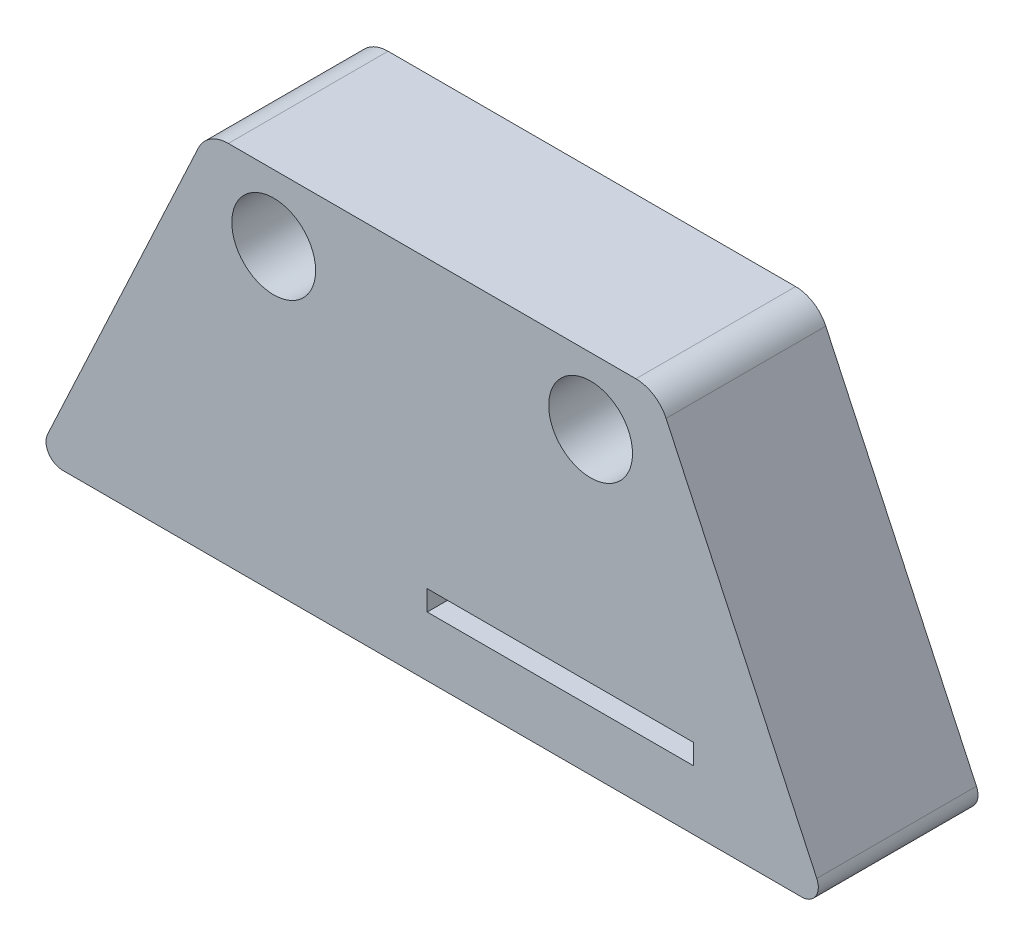
SolidWorks part; units mm, degrees
material "6061 Alloy"
ref_plane "Front Plane" through (0, 0, 0) normal (0, 0, 1) x (1, 0, 0)
ref_plane "Top Plane" through (0, 0, 0) normal (0, 1, 0) x (1, 0, 0)
ref_plane "Right Plane" through (0, 0, 0) normal (1, 0, 0) x (0, 0, -1)
sketch "Sketch1" plane through (0, 0, 0) normal (0, 0, 1) x (1, 0, 0)
  line L0 (0, 0) -> (-38.1, 0)
  line L1 (0, 0) -> (9.525, 0)
  line L2 (9.525, 0) -> (9.525, 10)
  line L3 (9.525, 10) -> (-38.1, 10)
  line L4 (-38.1, 10) -> (-38.1, 0)
  line L5 (-38.1, 0) -> (-38.1, -45)
  line L6 (-38.1, -45) -> (9.525, -45)
  line L7 (9.525, -45) -> (9.525, 0)
  line L8 (-38.1, 10) -> (-44.9146, 10)
  line L9 (-49.4462, 7.1131) -> (-72.0885, -41.4435)
  line L10 (-69.8227, -45) -> (-38.1, -45)
  line L11 (9.525, 10) -> (16.3396, 10)
  line L12 (20.8712, 7.1131) -> (43.5135, -41.4435)
  line L13 (41.2477, -45) -> (9.525, -45)
  circle A0 centre (9.525, 0) radius 6.3
  circle A1 centre (-38.1, 0) radius 6.3
  arc A2 (-44.9146, 10) -> (-49.4462, 7.1131) centre (-44.9146, 5) ccw
  arc A3 (20.8712, 7.1131) -> (16.3396, 10) centre (16.3396, 5) ccw
  arc A4 (-69.8227, -45) -> (-72.0885, -41.4435) centre (-69.8227, -42.5) cw
  arc A5 (41.2477, -45) -> (43.5135, -41.4435) centre (41.2477, -42.5) ccw
  point P16 (-48.1, 10)
  point P19 (19.525, 10)
  dimension "D3" = 12.6
  dimension "D4" = 12.6
  dimension "D11" = 5
  dimension "D12" = 5
  dimension "D13" = 2.5
  dimension "D14" = 2.5
  dimension "D1" = 38.1
  dimension "D2" = 9.525
  dimension "D5" = 10
  dimension "D6" = 45
  dimension "D7" = 10
  dimension "D8" = 65
  dimension "D9" = 10
  dimension "D10" = 65
extrude "Boss-Extrude1" add sketch "Sketch1" along normal blind 20 and the other way blind 4 contours A1 L4 L8 L9 L10 L5 | A1 L5 L6 L7 A0 L1 L0 | A0 L7 L13 L12 L11 L2 | A1 L0 L1 A0 L2 L3 L4
sketch "Sketch2" plane through (0, 0, 20) normal (0, 0, 1) x (1, 0, 0)
  line L1 (-69.8227, -45) -> (41.2477, -45) construction
  line L2 (0, -45) -> (24.975, -45)
  line L3 (24.975, -45) -> (24.975, -33)
  line L4 (24.975, -33) -> (-15.025, -33)
  line L5 (-15.025, -33) -> (-15.025, -36.0451)
  line L6 (-15.025, -36.0451) -> (24.975, -36.0451)
  dimension "D1" = 12
  dimension "D2" = 3.0451
  dimension "D3" = 40
extrude "Cut-Extrude1" cut sketch "Sketch2" against normal blind 10
